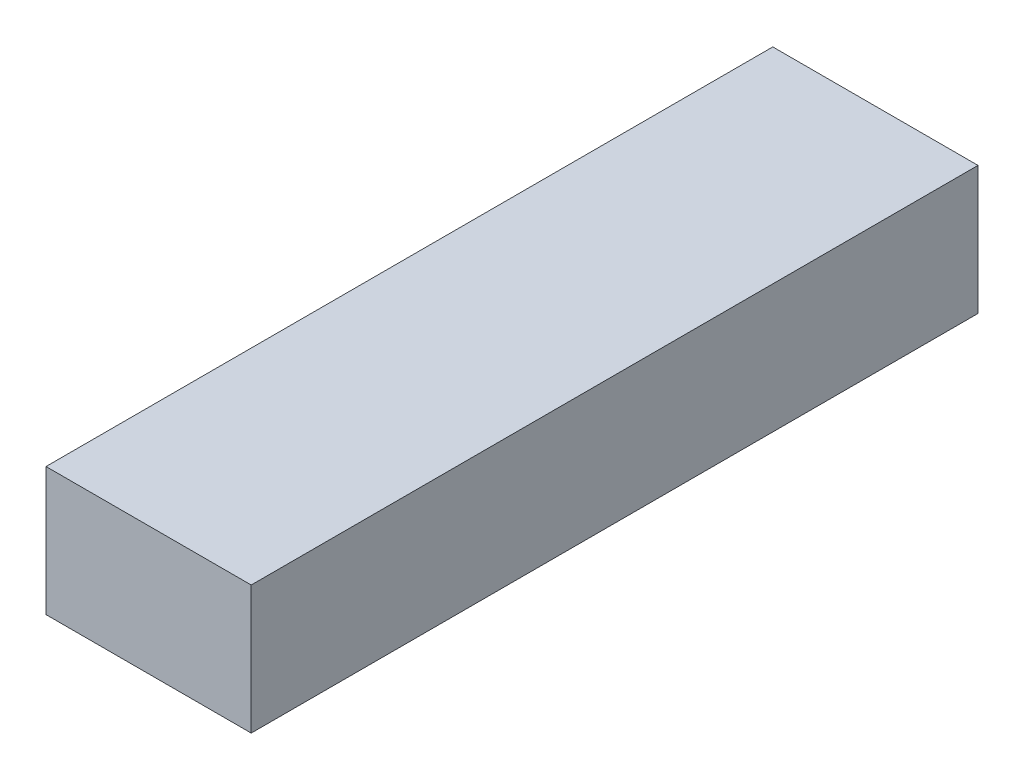
SolidWorks part; units mm, degrees
ref_plane "前视基准面" through (0, 0, 0) normal (0, 0, 1) x (1, 0, 0)
ref_plane "上视基准面" through (0, 0, 0) normal (0, 1, 0) x (1, 0, 0)
ref_plane "右视基准面" through (0, 0, 0) normal (1, 0, 0) x (0, 0, -1)
other "Configuration Table"
sketch "草图1" plane through (0, 0, 0) normal (0, 0, 1) x (1, 0, 0)
  line L1 (-24, 15) -> (24, 15)
  line L2 (-24, 15) -> (-24, -15)
  line L3 (-24, -15) -> (24, -15)
  line L4 (24, 15) -> (24, -15)
  line L5 (-24, 15) -> (24, -15) construction
  line L6 (-24, -15) -> (24, 15) construction
  point P0 (0, 0)
  dimension "D1" = 48
  dimension "D2" = 30
extrude "凸台-拉伸1" add sketch "草图1" along normal blind 170
